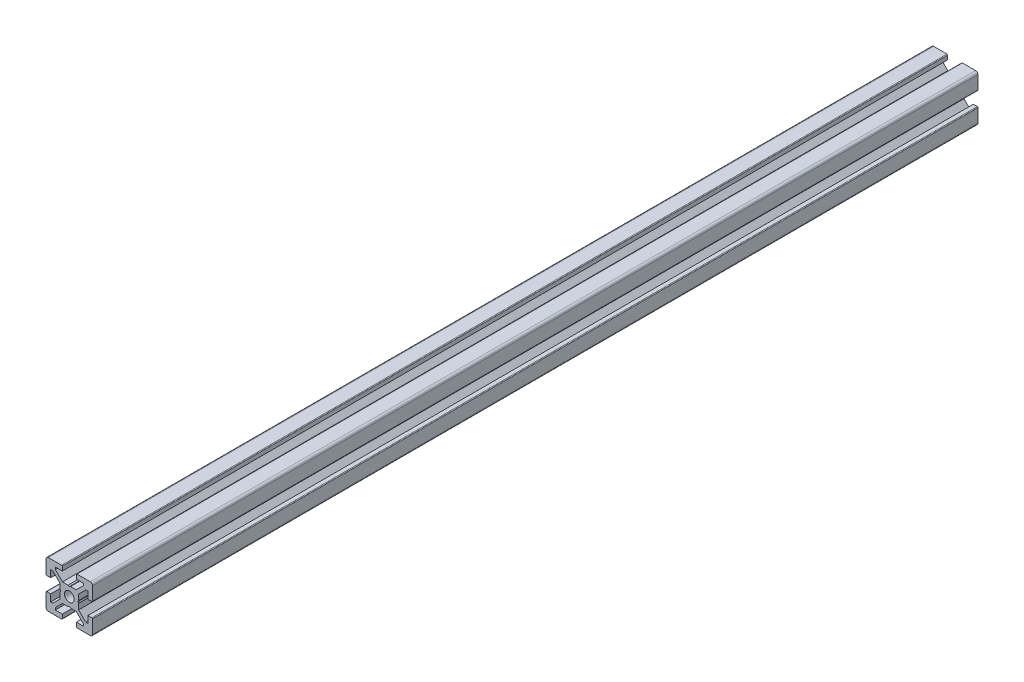
SolidWorks part; units mm, degrees
ref_plane "Front Plane" through (0, 0, 0) normal (0, 0, 1) x (1, 0, 0)
ref_plane "Top Plane" through (0, 0, 0) normal (0, 1, 0) x (1, 0, 0)
ref_plane "Right Plane" through (0, 0, 0) normal (1, 0, 0) x (0, 0, -1)
ref_plane "Plane1" through (0, 0, 0) normal (0, 0, 1) x (1, 0, 0)
sketch "Sketch1" plane through (0, 0, 0) normal (0, 0, 1) x (1, 0, 0)
  line L0 (-10, 9) -> (-10, 3.3)
  line L1 (-9.7, 3) -> (-8, 3)
  line L2 (-8, 3) -> (-8, 6)
  line L3 (-8, 6) -> (-7.0607, 6)
  line L4 (-7.0607, 6) -> (-4, 2.9393)
  line L5 (-4, 2.9393) -> (-4, 0.5196)
  line L6 (-4, 0.5196) -> (-3.7, 0)
  line L7 (-3.7, 0) -> (-4, -0.5196)
  line L8 (-4, -0.5196) -> (-4, -2.9393)
  line L9 (-4, -2.9393) -> (-7.0607, -6)
  line L10 (-7.0607, -6) -> (-8, -6)
  line L11 (-8, -6) -> (-8, -3)
  line L12 (-8, -3) -> (-9.7, -3)
  line L13 (-10, -3.3) -> (-10, -9)
  line L14 (-9, -10) -> (-3.3, -10)
  line L15 (-3, -9.7) -> (-3, -8)
  line L16 (-3, -8) -> (-6, -8)
  line L17 (-6, -8) -> (-6, -7.0607)
  line L18 (-6, -7.0607) -> (-2.9393, -4)
  line L19 (-2.9393, -4) -> (-0.5196, -4)
  line L20 (-0.5196, -4) -> (0, -3.7)
  line L21 (0, -3.7) -> (0.5196, -4)
  line L22 (0.5196, -4) -> (2.9393, -4)
  line L23 (2.9393, -4) -> (6, -7.0607)
  line L24 (6, -7.0607) -> (6, -8)
  line L25 (6, -8) -> (3, -8)
  line L26 (3, -8) -> (3, -9.7)
  line L27 (3.3, -10) -> (9, -10)
  line L28 (10, -9) -> (10, -3.3)
  line L29 (9.7, -3) -> (8, -3)
  line L30 (8, -3) -> (8, -6)
  line L31 (8, -6) -> (7.0606, -6)
  line L32 (7.0606, -6) -> (4, -2.9393)
  line L33 (4, -2.9393) -> (4, -0.5196)
  line L34 (4, -0.5196) -> (3.7, 0)
  line L35 (3.7, 0) -> (4, 0.5196)
  line L36 (4, 0.5196) -> (4, 2.9393)
  line L37 (4, 2.9393) -> (7.0607, 6)
  line L38 (7.0607, 6) -> (8, 6)
  line L39 (8, 6) -> (8, 3)
  line L40 (8, 3) -> (9.7, 3)
  line L41 (10, 3.3) -> (10, 9)
  line L42 (9, 10) -> (3.3, 10)
  line L43 (3, 9.7) -> (3, 8)
  line L44 (3, 8) -> (6, 8)
  line L45 (6, 8) -> (6, 7.0607)
  line L46 (6, 7.0607) -> (2.9393, 4)
  line L47 (2.9393, 4) -> (0.5196, 4)
  line L48 (0.5196, 4) -> (0, 3.7)
  line L49 (0, 3.7) -> (-0.5196, 4)
  line L50 (-0.5196, 4) -> (-2.9394, 4)
  line L51 (-2.9394, 4) -> (-6, 7.0606)
  line L52 (-6, 7.0606) -> (-6, 8)
  line L53 (-6, 8) -> (-3, 8)
  line L54 (-3, 8) -> (-3, 9.7)
  line L55 (-3.3, 10) -> (-9, 10)
  arc A0 (-10, 3.3) -> (-9.7, 3) centre (-9.7, 3.3) ccw
  arc A1 (-9.7, -3) -> (-10, -3.3) centre (-9.7, -3.3) ccw
  arc A2 (-10, -9) -> (-9, -10) centre (-9, -9) ccw
  arc A3 (-3.3, -10) -> (-3, -9.7) centre (-3.3, -9.7) ccw
  arc A4 (3, -9.7) -> (3.3, -10) centre (3.3, -9.7) ccw
  arc A5 (9, -10) -> (10, -9) centre (9, -9) ccw
  arc A6 (10, -3.3) -> (9.7, -3) centre (9.7, -3.3) ccw
  arc A7 (9.7, 3) -> (10, 3.3) centre (9.7, 3.3) ccw
  arc A8 (10, 9) -> (9, 10) centre (9, 9) ccw
  arc A9 (3.3, 10) -> (3, 9.7) centre (3.3, 9.7) ccw
  arc A10 (-3, 9.7) -> (-3.3, 10) centre (-3.3, 9.7) ccw
  arc A11 (-9, 10) -> (-10, 9) centre (-9, 9) ccw
extrude "Boss-Extrude1" add sketch "Sketch1" against normal blind 380
ref_plane "Plane2" through (0, 0, 0) normal (1, 0, 0) x (0, 0, -1)
sketch "Sketch2" plane through (0, 0, 0) normal (1, 0, 0) x (0, 0, -1)
  line L0 (0, 0) -> (0, 2.1)
  line L1 (0, 2.1) -> (400, 2.1)
  line L2 (400, 2.1) -> (400, 0)
  line L3 (400, 0) -> (0, 0)
  line L4 (400, 0) -> (0, 0) construction
revolve "Cut-Revolve1" cut sketch "Sketch2" angle 360 about L4
